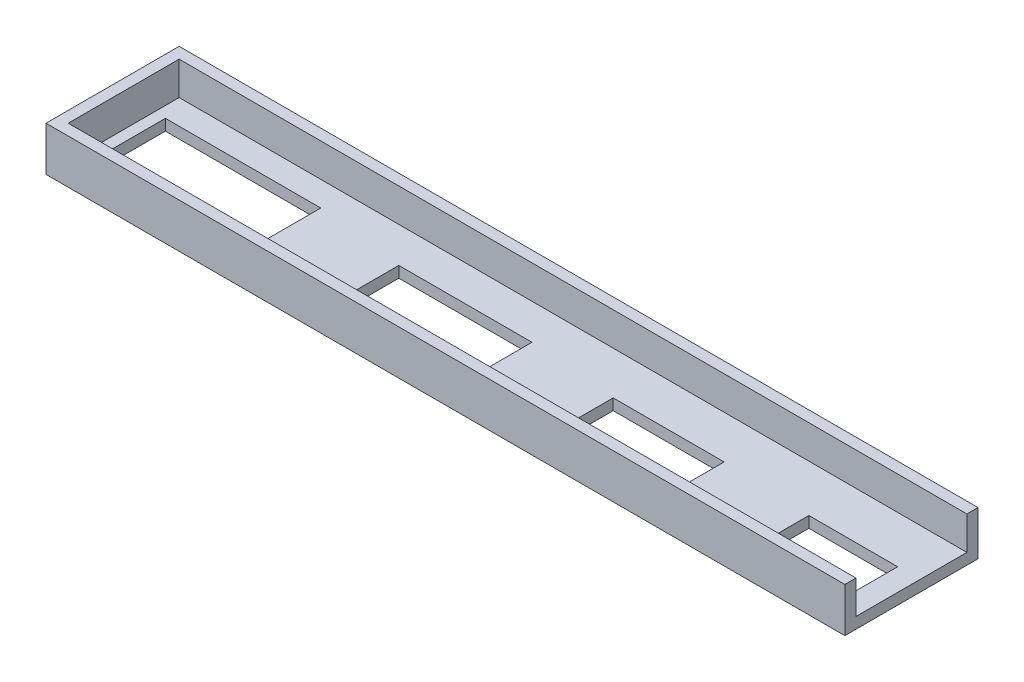
SolidWorks part; units mm, degrees
ref_plane "Front Plane" through (0, 0, 0) normal (0, 0, 1) x (1, 0, 0)
ref_plane "Top Plane" through (0, 0, 0) normal (0, 1, 0) x (1, 0, 0)
ref_plane "Right Plane" through (0, 0, 0) normal (1, 0, 0) x (0, 0, -1)
sketch "Sketch1" plane through (0, 0, 0) normal (0, 1, 0) x (1, 0, 0)
  line L1 (0, 0) -> (228.6, 0)
  line L2 (0, 0) -> (0, 38.1)
  line L3 (0, 38.1) -> (228.6, 38.1)
  line L4 (228.6, 0) -> (228.6, 38.1)
  dimension "D1" = 38.1
  dimension "D2" = 228.6
extrude "Boss-Extrude1" add sketch "Sketch1" against normal blind 12.7
shell "Shell1" thickness 3.175
sketch "Sketch3" plane through (0, 0, 0) normal (0, 1, 0) x (1, 0, 0)
  line L0 (228.6, 0) -> (228.6, 38.1) construction
  line L1 (225.425, 34.925) -> (228.6, 34.925)
  line L2 (225.425, 34.925) -> (225.425, 3.175)
  line L3 (225.425, 3.175) -> (228.6, 3.175)
  line L4 (228.6, 34.925) -> (228.6, 3.175)
extrude "Cut-Extrude1" cut sketch "Sketch3" against normal up to surface (9.525 mm away) up to face at (114.3, -9.525, -19.05)
sketch "Sketch4" plane through (0, -9.525, 0) normal (0, 1, 0) x (1, 0, 0)
  line L0 (3.175, 3.175) -> (228.6, 3.175) construction
  line L1 (222.25, 5.08) -> (196.85, 5.08)
  line L2 (222.25, 5.08) -> (222.25, 21.463)
  line L3 (222.25, 21.463) -> (196.85, 21.463)
  line L4 (196.85, 5.08) -> (196.85, 21.463)
  line L5 (228.6, 3.175) -> (228.6, 34.925) construction
  line L6 (3.175, 3.175) -> (228.6, 3.175) construction
  line L7 (139.7, 22.606) -> (171.45, 22.606)
  line L8 (139.7, 22.606) -> (139.7, 5.08)
  line L9 (139.7, 5.08) -> (171.45, 5.08)
  line L10 (171.45, 22.606) -> (171.45, 5.08)
  line L11 (76.2, 24.765) -> (114.3, 24.765)
  line L12 (76.2, 24.765) -> (76.2, 5.08)
  line L13 (76.2, 5.08) -> (114.3, 5.08)
  line L14 (114.3, 24.765) -> (114.3, 5.08)
  line L16 (6.35, 27.813) -> (50.8, 27.813)
  line L17 (6.35, 27.813) -> (6.35, 5.08)
  line L18 (6.35, 5.08) -> (50.8, 5.08)
  line L19 (50.8, 27.813) -> (50.8, 5.08)
  circle A0 centre (211.442, 12.1285) radius 8.9535 construction
  circle A1 centre (157.4102, 12.7) radius 9.525 construction
  circle A2 centre (96.4213, 13.7795) radius 10.6045 construction
  circle A3 centre (28.7378, 15.3035) radius 12.1285 construction
  point P26 (30.4858, 16.4465)
  point P27 (308.9273, 14.9225)
  point P28 (314.7012, 15.3035)
  point P29 (157.4102, 13.843)
  point P34 (96.4213, 12.7)
  point P35 (28.575, 13.7795)
  point P36 (211.442, 12.1285)
  dimension "D1" = 17.907
  dimension "D7" = 19.05
  dimension "D15" = 21.209
  dimension "D16" = 44.45
  dimension "D20" = 24.257
  dimension "D2" = 18.288
  dimension "D3" = 1.905
  dimension "D4" = 6.35
  dimension "D5" = 25.4
  dimension "D6" = 31.75
  dimension "D8" = 19.431
  dimension "D9" = 1.905
  dimension "D10" = 25.4
  dimension "D11" = 38.1
  dimension "D12" = 25.4
  dimension "D13" = 21.59
  dimension "D14" = 1.905
  dimension "D17" = 25.4
  dimension "D18" = 24.638
  dimension "D19" = 1.905
extrude "Cut-Extrude2" cut sketch "Sketch4" against normal through all
